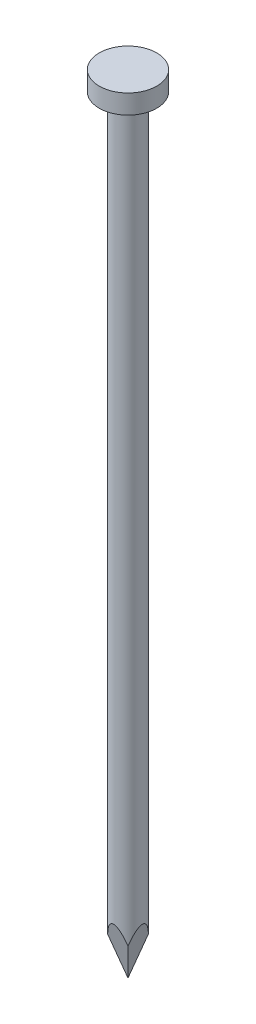
SolidWorks part; units mm, degrees
ref_plane "Спереди" through (0, 0, 0) normal (0, 0, 1) x (1, 0, 0)
ref_plane "Сверху" through (0, 0, 0) normal (0, 1, 0) x (1, 0, 0)
ref_plane "Справа" through (0, 0, 0) normal (1, 0, 0) x (0, 0, -1)
sketch "Эскиз1" plane through (0, 0, 0) normal (0, 1, 0) x (1, 0, 0)
  circle A0 centre (0, 0) radius 0.75
  dimension "D1" = 1.5
extrude "Бобышка-Вытянуть1" add sketch "Эскиз1" against normal blind 40
sketch "Эскиз2" plane through (0, 0, 0) normal (0, 1, 0) x (1, 0, 0)
  circle A0 centre (0, 0) radius 1.5
  dimension "D1" = 3
extrude "Бобышка-Вытянуть2" add sketch "Эскиз2" along normal blind 1
sketch "Эскиз5" plane through (0, 0, 0) normal (1, 0, 0) x (0, 0, -1)
  line L0 (-1.2013, -35.5166) -> (-1.2013, -40.5166)
  line L1 (-1.2013, -40.5166) -> (1.2013, -40.5166)
  line L2 (1.2013, -40.5166) -> (1.2013, -35.5166)
  line L3 (1.2013, -35.5166) -> (0, -40)
  line L4 (-0.75, -40) -> (0.75, -40) construction
  line L5 (0, -40) -> (-1.2013, -35.5166)
  dimension "D1" = 5
extrude "Вырез-Вытянуть2" cut sketch "Эскиз5" against normal through all and the other way through all
sketch "Эскиз7" plane through (0, 0, 0) normal (0, 0, 1) x (1, 0, 0)
  line L0 (-1.2675, -35.2696) -> (-1.2675, -40.2696)
  line L1 (-1.2675, -40.2696) -> (1.2675, -40.2696)
  line L2 (1.2675, -40.2696) -> (1.2675, -35.2696)
  line L3 (1.2675, -35.2696) -> (0, -40)
  line L4 (-0.75, -40) -> (0.75, -40) construction
  line L5 (0, -40) -> (-1.2675, -35.2696)
  dimension "D1" = 5
extrude "Вырез-Вытянуть3" cut sketch "Эскиз7" against normal through all and the other way through all
